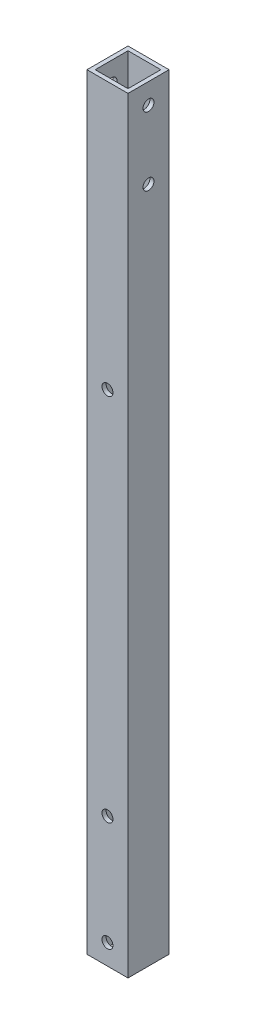
SolidWorks part; units mm, degrees
material "1060 合金"
ref_plane "正面" through (0, 0, 0) normal (0, 0, 1) x (1, 0, 0)
ref_plane "平面" through (0, 0, 0) normal (0, 1, 0) x (1, 0, 0)
ref_plane "右側面" through (0, 0, 0) normal (1, 0, 0) x (0, 0, -1)
sketch "ｽｹｯﾁ1" plane through (0, 0, 0) normal (0, 1, 0) x (1, 0, 0)
  line L1 (-7.5, -7.5) -> (7.5, -7.5)
  line L2 (-7.5, -7.5) -> (-7.5, 7.5)
  line L3 (-7.5, 7.5) -> (7.5, 7.5)
  line L4 (7.5, -7.5) -> (7.5, 7.5)
  line L5 (-7.5, -7.5) -> (7.5, 7.5) construction
  line L6 (-7.5, 7.5) -> (7.5, -7.5) construction
  point P0 (0, 0)
  dimension "D1" = 15
extrude "押し出し-薄板1" add sketch "ｽｹｯﾁ1" along normal blind 280 thin thin type one direction reverse wall 1.5
sketch "ｽｹｯﾁ2" plane through (7.5, 0, 0) normal (1, 0, 0) x (0, 0, -1)
  line L0 (0, 0) -> (0, 280) construction
  line L1 (-7.5, 280) -> (7.5, 280) construction
  circle A0 centre (0, 272.5) radius 2
  circle A1 centre (0, 247.5) radius 2
  dimension "D1" = 7.5
  dimension "D2" = 25
  dimension "D3" = 4
extrude "ｶｯﾄ - 押し出し1" cut sketch "ｽｹｯﾁ2" against normal through all
sketch "ｽｹｯﾁ3" plane through (0, 0, 7.5) normal (0, 0, 1) x (1, 0, 0)
  line L0 (0, 0) -> (0, 280) construction
  line L1 (-7.5, 280) -> (7.5, 280) construction
  line L2 (-7.5, 0) -> (7.5, 0) construction
  circle A0 centre (0, 7.5) radius 2
  circle A1 centre (0, 47.5) radius 2
  circle A3 centre (0, 182.5) radius 2
  dimension "D1" = 7.5
  dimension "D2" = 40
  dimension "D3" = 4
  dimension "D5" = 97.5
  dimension "D6" = 4
extrude "ｶｯﾄ - 押し出し2" cut sketch "ｽｹｯﾁ3" against normal through all
